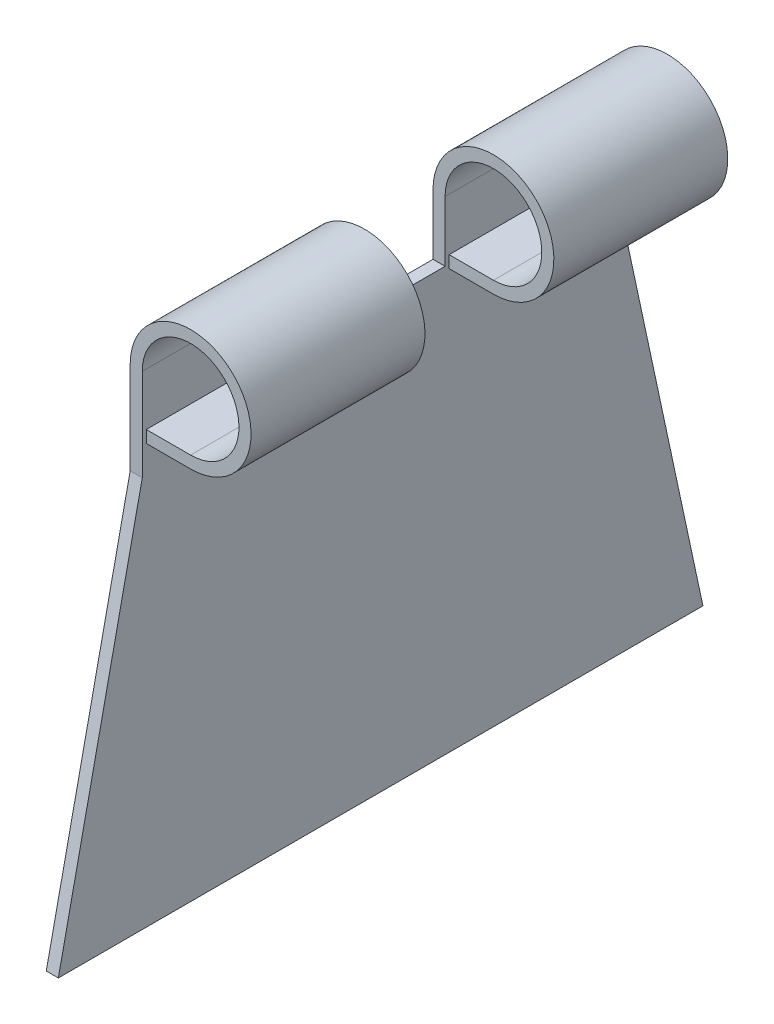
SolidWorks part; units mm, degrees
ref_plane "前视基准面" through (0, 0, 0) normal (0, 0, 1) x (1, 0, 0)
ref_plane "上视基准面" through (0, 0, 0) normal (0, 1, 0) x (1, 0, 0)
ref_plane "右视基准面" through (0, 0, 0) normal (1, 0, 0) x (0, 0, -1)
other "Configuration Table"
sketch "草图1" plane through (0, 0, 0) normal (0, 0, 1) x (1, 0, 0)
  line L0 (-7.5, -60) -> (-6, -60)
  line L2 (-7.5, 0) -> (-7.5, -60)
  line L3 (-6, 0) -> (-6, -60)
  line L4 (0, -6) -> (-5.5, -6)
  line L5 (-5.5, -6) -> (-5.5, -7.5)
  line L6 (-5.5, -7.5) -> (0, -7.5)
  arc A0 (0, -7.5) -> (-7.5, 0) centre (0, 0) ccw
  arc A1 (0, -6) -> (-6, 0) centre (0, 0) ccw
extrude "凸台-拉伸1" add sketch "草图1" along normal blind 80
ref_plane "基准面1" through (0, 0, 40) normal (0, 0, 1) x (1, 0, 0)
sketch "草图3" plane through (0, 0, 0) normal (0, 1, 0) x (1, 0, 0)
  line L0 (7.5, -40) -> (7.5, -32)
  line L1 (7.5, -80) -> (7.5, 0) construction
  line L2 (7.5, -32) -> (-7.5, -32)
  line L3 (-7.5, -80) -> (-7.5, 0) construction
  line L4 (-7.5, -32) -> (-7.5, -48)
  line L5 (-7.5, -48) -> (7.5, -48)
  line L6 (7.5, -48) -> (7.5, -40)
extrude "切除-拉伸1" cut sketch "草图3" along normal mid plane 15
sketch "草图5" plane through (-7.5, 0, 0) normal (-1, 0, 0) x (0, 0, 1)
  line L0 (80, -60) -> (69.5852, -11.441)
  line L1 (69.5852, -11.441) -> (69.5852, 7.4764)
  line L3 (80, 7.5) -> (80, -60)
  line L4 (40, -8.25) -> (40, 8.25) construction
  line L6 (10.4148, -11.441) -> (10.4148, 7.4764)
  line L7 (0, -60) -> (10.4148, -11.441)
  line L8 (0, 7.5) -> (0, -60)
  line L9 (69.5852, 7.4764) -> (69.5852, 9.6925)
  line L10 (69.5852, 9.6925) -> (80, 9.6925)
  line L11 (80, 9.6925) -> (80, 7.5)
  line L12 (10.4148, 7.4764) -> (10.4148, 9.6925)
  line L13 (10.4148, 9.6925) -> (0, 9.6925)
  line L14 (0, -8.25) -> (0, 8.25) construction
  line L15 (0, 9.6925) -> (0, 7.5)
extrude "切除-拉伸3" cut sketch "草图5" against normal through all
ref_plane "基准面2" through (0, 0, 80) normal (0, 0, 1) x (1, 0, 0)
